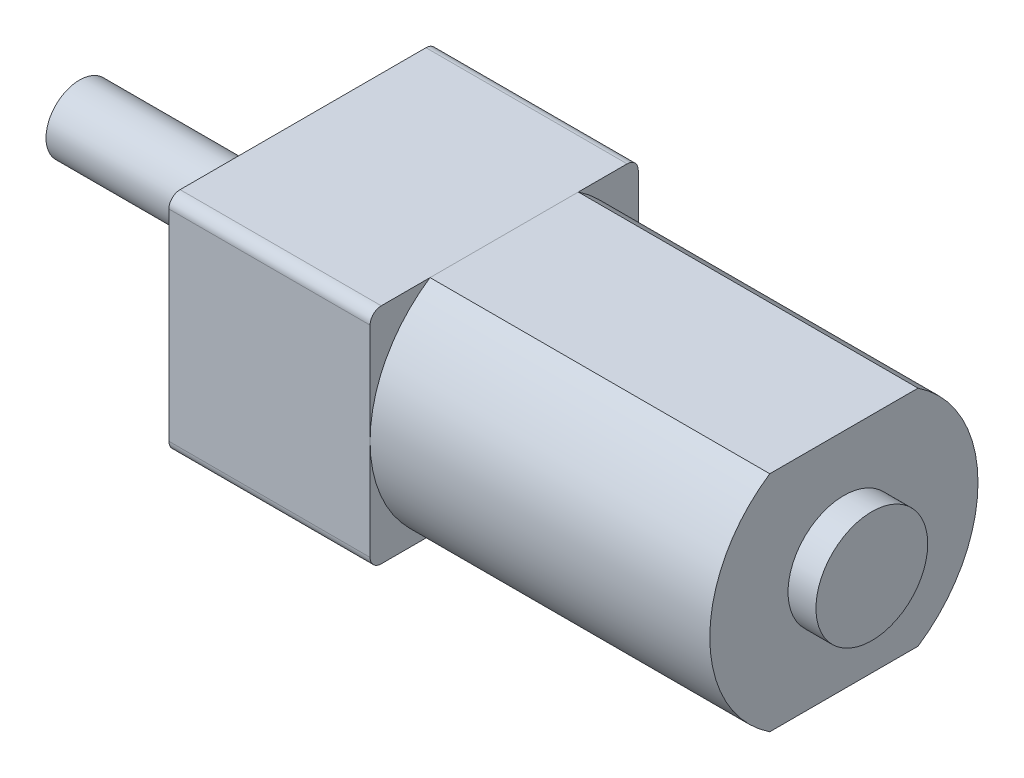
SolidWorks part; units mm, degrees
ref_plane "Front Plane" through (0, 0, 0) normal (0, 0, 1) x (1, 0, 0)
ref_plane "Top Plane" through (0, 0, 0) normal (0, 1, 0) x (1, 0, 0)
ref_plane "Right Plane" through (0, 0, 0) normal (1, 0, 0) x (0, 0, -1)
sketch "Sketch1" plane through (0, 0, 0) normal (1, 0, 0) x (0, 0, -1)
  line L0 (0, -8.8463) -> (0, 11.6483) construction
  line L1 (-3.3166, 5) -> (3.3166, 5)
  line L2 (-13.9699, 0) -> (16.0514, 0) construction
  line L3 (-3.3166, -5) -> (3.3166, -5)
  arc A0 (-3.3166, 5) -> (-3.3166, -5) centre (0, 0) ccw
  arc A1 (3.3166, -5) -> (3.3166, 5) centre (0, 0) ccw
  dimension "D1" = 12
  dimension "D2" = 5
extrude "Boss-Extrude1" add sketch "Sketch1" along normal blind 15.2
sketch "Sketch2" plane through (15.2, 0, 0) normal (1, 0, 0) x (0, 0, -1)
  circle A0 centre (0, 0) radius 2.5
  dimension "D1" = 5
extrude "Boss-Extrude2" add sketch "Sketch2" along normal blind 1.25
sketch "Sketch3" plane through (0, 0, 0) normal (-1, 0, 0) x (0, 0, 1)
  line L1 (-6, 5) -> (6, 5)
  line L2 (-6, 5) -> (-6, -5)
  line L3 (-6, -5) -> (6, -5)
  line L4 (6, 5) -> (6, -5)
  line L5 (-6, 5) -> (6, -5) construction
  line L6 (-6, -5) -> (6, 5) construction
  point P0 (0, 0)
  dimension "D1" = 10
  dimension "D2" = 12
extrude "Boss-Extrude3" add sketch "Sketch3" along normal blind 9 separate body
sketch "Sketch4" plane through (-9, 0, 0) normal (-1, 0, 0) x (0, 0, 1)
  circle A0 centre (0, 0) radius 2
  dimension "D1" = 4
extrude "Boss-Extrude4" add sketch "Sketch4" along normal blind 0.7
sketch "Sketch5" plane through (-9.7, 0, 0) normal (-1, 0, 0) x (0, 0, 1)
  line L0 (-1.118, -1) -> (1.118, -1)
  arc A0 (1.118, -1) -> (-1.118, -1) centre (0, 0) ccw
  dimension "D1" = 3
  dimension "D2" = 1
extrude "Boss-Extrude5" add sketch "Sketch5" along normal blind 9.3
fillet "Fillet1" radius 0.5 4 edges at (-4.5, -5, 6) (-4.5, -5, -6) (-4.5, 5, -6) (-4.5, 5, 6)
